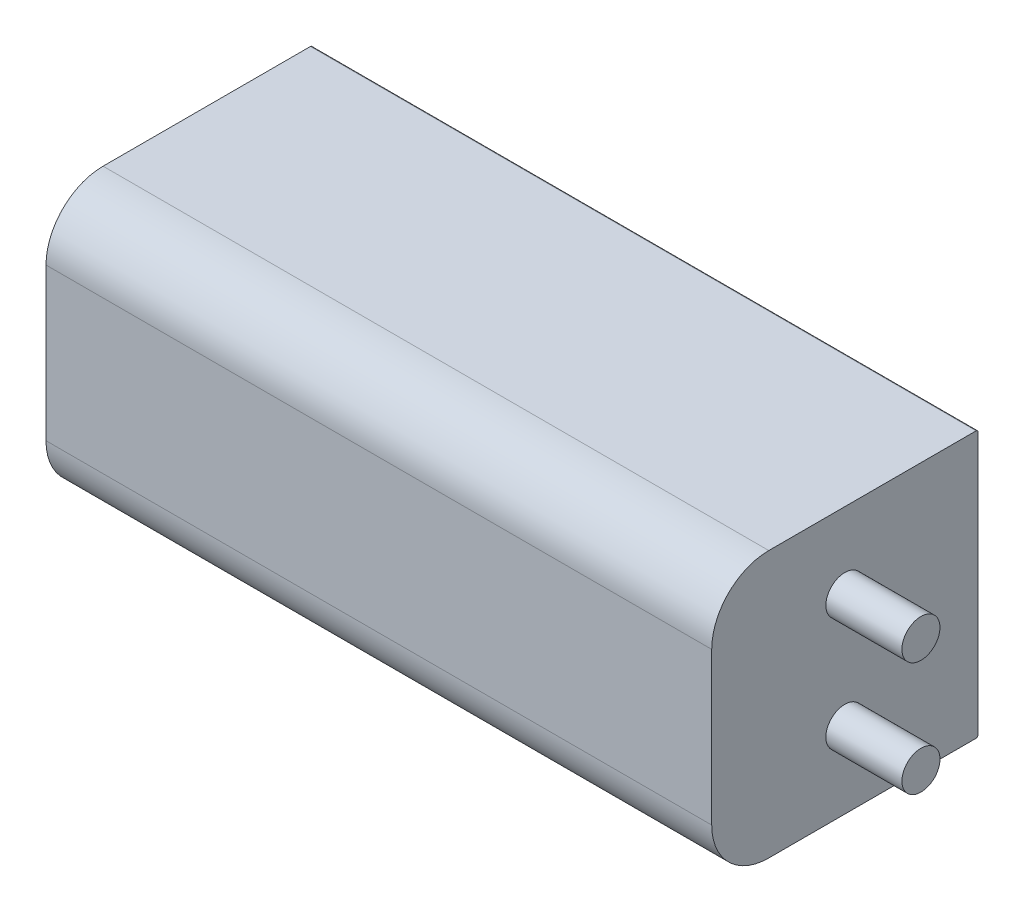
SolidWorks part; units mm, degrees
ref_plane "Front Plane" through (0, 0, 0) normal (0, 0, 1) x (1, 0, 0)
ref_plane "Top Plane" through (0, 0, 0) normal (0, 1, 0) x (1, 0, 0)
ref_plane "Right Plane" through (0, 0, 0) normal (1, 0, 0) x (0, 0, -1)
sketch "Sketch1" plane through (0, 0, 0) normal (0, 1, 0) x (1, 0, 0)
  line L1 (0, 0) -> (350, 0)
  line L2 (0, 0) -> (0, -140)
  line L3 (0, -140) -> (350, -140)
  line L4 (350, 0) -> (350, -140)
  circle A0 centre (0, -70) radius 69.995
  dimension "D3" = 139.99
  dimension "D1" = 140
  dimension "D2" = 350
extrude "Boss-Extrude1" add sketch "Sketch1" along normal blind 140 contours A0 L2 L3 L4 L1 | L2 A0
ref_plane "Plane1" through (0, 0, 0) normal (1, 0, 0) x (0, 0, -1)
sketch "Sketch2" plane through (0, 0, 0) normal (1, 0, 0) x (0, 0, -1)
  line L0 (0, 0) -> (-140, 0) construction
  line L3 (0, 140) -> (0, 0) construction
  line L4 (0, 140) -> (-140, 140) construction
  circle A0 centre (-70, 100) radius 10.5
  circle A1 centre (-70, 40) radius 10.5
  dimension "D5" = 21
  dimension "D6" = 21
  dimension "D4" = 40
  dimension "D1" = 70
  dimension "D2" = 70
  dimension "D3" = 40
extrude "Cut-Extrude3" cut sketch "Sketch2" along normal blind 41
fillet "Fillet2" radius 30 2 edges at (175, 140, 140) (175, 0, 140)
fillet "Fillet3" radius 1 2 edges at (175, 140, 0) (175, 0, 0)
sketch "Sketch3" plane through (350, 0, 0) normal (1, 0, 0) x (0, 0, -1)
  line L0 (0, 139) -> (0, 1) construction
  line L1 (-1, 140) -> (-110, 140) construction
  line L2 (-1, 0) -> (-110, 0) construction
  circle A0 centre (-70, 100) radius 10
  circle A1 centre (-70, 40) radius 10
  dimension "D3" = 20
  dimension "D4" = 20
  dimension "D6" = 40
  dimension "D1" = 70
  dimension "D2" = 70
  dimension "D5" = 40
extrude "Boss-Extrude3" add sketch "Sketch3" along normal blind 40
